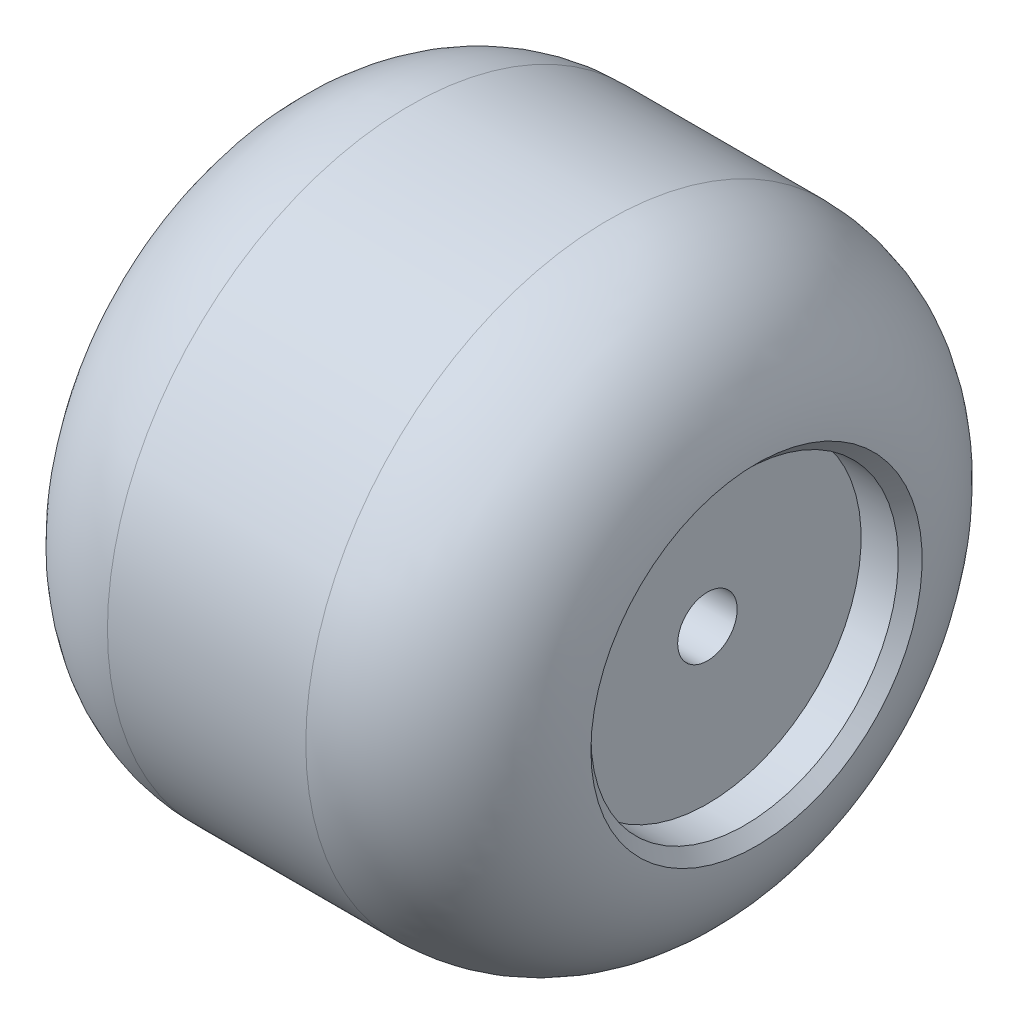
SolidWorks part; units mm, degrees
ref_plane "Front Plane" through (0, 0, 0) normal (0, 0, 1) x (1, 0, 0)
ref_plane "Top Plane" through (0, 0, 0) normal (0, 1, 0) x (1, 0, 0)
ref_plane "Right Plane" through (0, 0, 0) normal (1, 0, 0) x (0, 0, -1)
sketch "Sketch1" plane through (0, 0, 0) normal (0, 1, 0) x (1, 0, 0)
  line L0 (20, 6.7) -> (19.5, 6.2)
  line L1 (0, 1.2) -> (18, 1.2)
  line L2 (0, 1.2) -> (0, 6.2)
  line L3 (6, 12.2) -> (14, 12.2)
  line L4 (20, 6.7) -> (20, 6.2)
  line L5 (19.5, 6.2) -> (18, 6.2)
  line L8 (18, 6.2) -> (18, 1.2)
  line L9 (0, 0) -> (21.7304, 0) construction
  arc A0 (20, 6.2) -> (14, 12.2) centre (14, 6.2) ccw
  arc A1 (0, 6.2) -> (6, 12.2) centre (6, 6.2) cw
  point P7 (20, 12.2)
  point P10 (0, 12.2)
  dimension "D3" = 6
  dimension "D4" = 6
  dimension "D1" = 11
  dimension "D2" = 20
  dimension "D5" = 1.5
  dimension "D6" = 5
  dimension "D7" = 45
  dimension "D8" = 2
  dimension "D9" = 1.2
  dimension "D10" = 18
revolve "Revolve1" add sketch "Sketch1" angle 360 about L9
